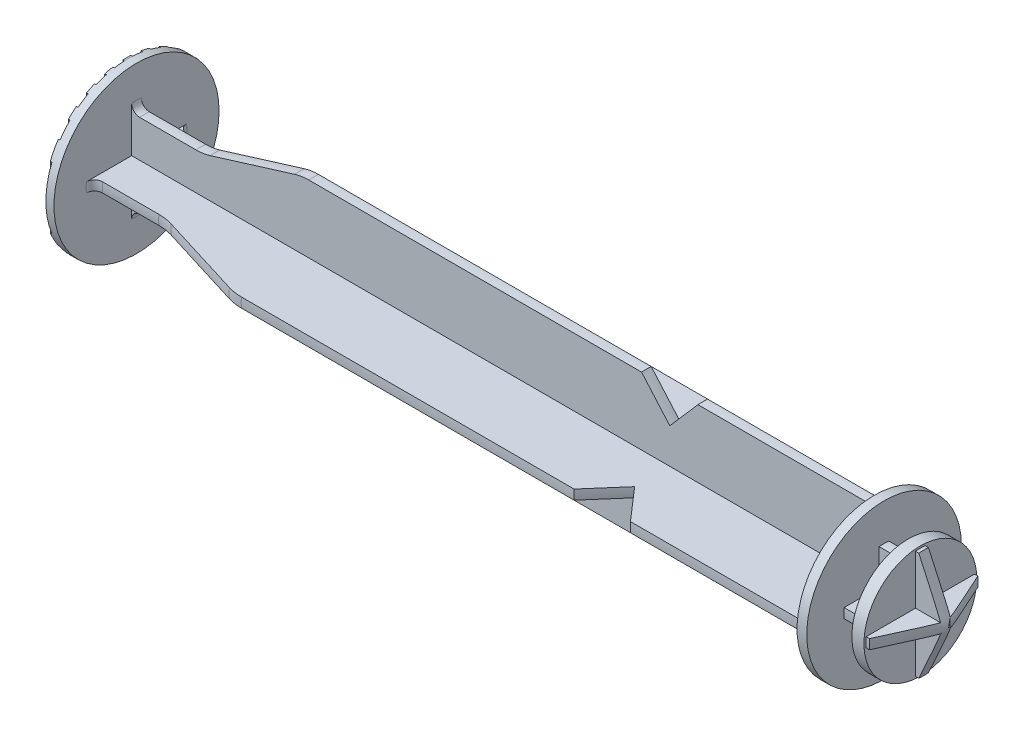
SolidWorks part; units mm, degrees
material "Polyethylene Cross-Linked"
ref_plane "Front Plane" through (0, 0, 0) normal (0, 0, 1) x (1, 0, 0)
ref_plane "Top Plane" through (0, 0, 0) normal (0, 1, 0) x (1, 0, 0)
ref_plane "Right Plane" through (0, 0, 0) normal (1, 0, 0) x (0, 0, -1)
sketch "Sketch1" plane through (0, 0, 0) normal (0, 0, 1) x (1, 0, 0)
  line L0 (102, 0) -> (-102, 0) construction
  line L1 (0, 0) -> (0, 10.25)
  line L2 (0, 10.25) -> (1.2, 10.25)
  line L3 (1.2, 10.25) -> (1.2, 6.25)
  line L4 (2.2, 5.25) -> (9.2, 5.25)
  line L5 (10.9633, 5.5149) -> (21.4367, 8.7351)
  line L6 (23.2, 9) -> (64.5, 9)
  line L7 (64.5, 9) -> (68, 5)
  line L8 (68, 5) -> (71.5, 9)
  line L9 (71.5, 9) -> (92.8, 9)
  line L10 (92.8, 9) -> (92.8, 9.6)
  line L11 (92.8, 9.6) -> (94, 9.6)
  line L12 (94, 9.6) -> (94, 5)
  line L13 (94, 5) -> (97, 5)
  line L14 (97, 5) -> (97, 7)
  line L15 (97, 7) -> (98.8, 7)
  line L16 (98.8, 7) -> (102, 0)
  line L17 (0, 0) -> (102, 0)
  arc A0 (1.2, 6.25) -> (2.2, 5.25) centre (2.2, 6.25) ccw
  arc A1 (21.4367, 8.7351) -> (23.2, 9) centre (23.2, 3) cw
  arc A2 (9.2, 5.25) -> (10.9633, 5.5149) centre (9.2, 11.25) ccw
  point P3 (0, 0)
  point P4 (0, 0)
  dimension "D14" = 1
  dimension "D15" = 6
  dimension "D1" = 1.2
  dimension "D2" = 8
  dimension "D3" = 20.5
  dimension "D4" = 10.5
  dimension "D5" = 102
  dimension "D6" = 10
  dimension "D7" = 7
  dimension "D8" = 18
  dimension "D9" = 19.2
  dimension "D10" = 10
  dimension "D11" = 14
  dimension "D12" = 34
  dimension "D13" = 5
  dimension "D16" = 8
  dimension "D17" = 22
  dimension "D18" = 3.2
revolve "Revolve1" add sketch "Sketch1" angle 360 about L0
sketch "Sketch2" plane through (1.2, 0, 0) normal (1, 0, 0) x (0, 0, -1)
  line L0 (17.7295, 0) -> (-17.7295, 0) construction
  line L1 (0, -17.5817) -> (0, 17.5817) construction
  line L2 (-0.6, 10.2324) -> (-0.6, 0.6)
  line L3 (-0.6, 0.6) -> (-10.2324, 0.6)
  line L4 (0.6, 0.6) -> (0.6, 10.2324)
  line L5 (10.2324, 0.6) -> (0.6, 0.6)
  line L6 (0.6, -0.6) -> (10.2324, -0.6)
  line L7 (0.6, -10.2324) -> (0.6, -0.6)
  line L8 (-0.6, -0.6) -> (-0.6, -10.2324)
  line L9 (-10.2324, -0.6) -> (-0.6, -0.6)
  circle A0 centre (0, 0) radius 10.25 construction
  arc A1 (-10.2324, 0.6) -> (-10.2324, -0.6) centre (0, 0) ccw
  arc A2 (0.6, 10.2324) -> (-0.6, 10.2324) centre (0, 0) ccw
  arc A3 (10.2324, -0.6) -> (10.2324, 0.6) centre (0, 0) ccw
  arc A4 (-0.6, -10.2324) -> (0.6, -10.2324) centre (0, 0) ccw
  point P5 (0, 0)
  point P9 (0, 0)
  point P27 (0, 0)
  dimension "D3" = 1.2
  dimension "D2" = 4
extrude "Cut-Extrude1" cut sketch "Sketch2" along normal up to surface (91.6 mm away) flip side to cut up to face at (92.8, 0, -9)
sketch "Sketch3" plane through (0, 0, 0) normal (-1, 0, 0) x (0, 0, 1)
  line L0 (2.75, -10.2378) -> (1.75, -10.2378)
  line L1 (0.5, -10.2378) -> (-0.5, -10.2378)
  line L2 (0.5, -10.2378) -> (0.5, 10.2378)
  line L3 (0.5, 10.2378) -> (-0.5, 10.2378)
  line L4 (-0.5, -10.2378) -> (-0.5, 10.2378)
  line L5 (0.5, -10.2378) -> (-0.5, 10.2378) construction
  line L6 (0.5, 10.2378) -> (-0.5, -10.2378) construction
  line L7 (1.75, -10.2378) -> (1.75, 10.2378)
  line L8 (2.75, 10.2378) -> (1.75, 10.2378)
  line L9 (2.75, -10.2378) -> (2.75, 10.2378)
  line L10 (5, -10.2378) -> (4, -10.2378)
  line L11 (4, -10.2378) -> (4, 10.2378)
  line L12 (5, 10.2378) -> (4, 10.2378)
  line L13 (5, -10.2378) -> (5, 10.2378)
  line L14 (7.25, -10.2378) -> (6.25, -10.2378)
  line L15 (6.25, -10.2378) -> (6.25, 10.2378)
  line L16 (7.25, 10.2378) -> (6.25, 10.2378)
  line L17 (7.25, -10.2378) -> (7.25, 10.2378)
  line L18 (9.5, -10.2378) -> (8.5, -10.2378)
  line L19 (8.5, -10.2378) -> (8.5, 10.2378)
  line L20 (9.5, 10.2378) -> (8.5, 10.2378)
  line L21 (9.5, -10.2378) -> (9.5, 10.2378)
  line L22 (11.75, -10.2378) -> (10.75, -10.2378)
  line L23 (10.75, -10.2378) -> (10.75, 10.2378)
  line L24 (11.75, 10.2378) -> (10.75, 10.2378)
  line L25 (11.75, -10.2378) -> (11.75, 10.2378)
  line L26 (14, -10.2378) -> (13, -10.2378)
  line L27 (13, -10.2378) -> (13, 10.2378)
  line L28 (14, 10.2378) -> (13, 10.2378)
  line L29 (14, -10.2378) -> (14, 10.2378)
  line L30 (-1.75, -10.2378) -> (-2.75, -10.2378)
  line L31 (-2.75, -10.2378) -> (-2.75, 10.2378)
  line L32 (-1.75, 10.2378) -> (-2.75, 10.2378)
  line L33 (-1.75, -10.2378) -> (-1.75, 10.2378)
  line L34 (-4, -10.2378) -> (-5, -10.2378)
  line L35 (-5, -10.2378) -> (-5, 10.2378)
  line L36 (-4, 10.2378) -> (-5, 10.2378)
  line L37 (-4, -10.2378) -> (-4, 10.2378)
  line L38 (-6.25, -10.2378) -> (-7.25, -10.2378)
  line L39 (-7.25, -10.2378) -> (-7.25, 10.2378)
  line L40 (-6.25, 10.2378) -> (-7.25, 10.2378)
  line L41 (-6.25, -10.2378) -> (-6.25, 10.2378)
  line L42 (-8.5, -10.2378) -> (-9.5, -10.2378)
  line L43 (-9.5, -10.2378) -> (-9.5, 10.2378)
  line L44 (-8.5, 10.2378) -> (-9.5, 10.2378)
  line L45 (-8.5, -10.2378) -> (-8.5, 10.2378)
  line L46 (-10.75, -10.2378) -> (-11.75, -10.2378)
  line L47 (-11.75, -10.2378) -> (-11.75, 10.2378)
  line L48 (-10.75, 10.2378) -> (-11.75, 10.2378)
  line L49 (-10.75, -10.2378) -> (-10.75, 10.2378)
  line L50 (-13, -10.2378) -> (-14, -10.2378)
  line L51 (-14, -10.2378) -> (-14, 10.2378)
  line L52 (-13, 10.2378) -> (-14, 10.2378)
  line L53 (-13, -10.2378) -> (-13, 10.2378)
  circle A0 centre (0, 0) radius 10.25 construction
  point P0 (0, 0)
  dimension "D1" = 1
  dimension "D3" = 2.25
  dimension "D2" = 7
  dimension "D4" = 7
extrude "Cut-Extrude2" cut sketch "Sketch3" against normal blind 0.2 flip side to cut
sketch "Sketch4" plane through (94, 0, 0) normal (1, 0, 0) x (0, 0, -1)
  line L8 (0.6, 0.6) -> (0.6, 10.2324)
  line L9 (-0.6, 10.2324) -> (-0.6, 0.6)
  line L10 (-0.6, 0.6) -> (-10.2324, 0.6)
  line L11 (-10.2324, -0.6) -> (-0.6, -0.6)
  line L12 (-0.6, -0.6) -> (-0.6, -10.2324)
  line L13 (0.6, -10.2324) -> (0.6, -0.6)
  line L14 (0.6, -0.6) -> (10.2324, -0.6)
  line L15 (10.2324, 0.6) -> (0.6, 0.6)
  line L16 (0.6, 0.6) -> (0.6, 10.2324)
  line L17 (-0.6, 10.2324) -> (-0.6, 0.6)
  line L18 (-0.6, 0.6) -> (-10.2324, 0.6)
  line L19 (-10.2324, -0.6) -> (-0.6, -0.6)
  line L20 (-0.6, -0.6) -> (-0.6, -10.2324)
  line L21 (0.6, -10.2324) -> (0.6, -0.6)
  line L22 (0.6, -0.6) -> (10.2324, -0.6)
  line L23 (10.2324, 0.6) -> (0.6, 0.6)
  arc A4 (0.6, 10.2324) -> (-0.6, 10.2324) centre (0, 0) ccw
  arc A5 (-10.2324, 0.6) -> (-10.2324, -0.6) centre (0, 0) ccw
  arc A6 (-0.6, -10.2324) -> (0.6, -10.2324) centre (0, 0) ccw
  arc A7 (10.2324, -0.6) -> (10.2324, 0.6) centre (0, 0) ccw
  arc A8 (0.6, 10.2324) -> (-0.6, 10.2324) centre (0, 0) ccw
  arc A9 (-10.2324, 0.6) -> (-10.2324, -0.6) centre (0, 0) ccw
  arc A10 (-0.6, -10.2324) -> (0.6, -10.2324) centre (0, 0) ccw
  arc A11 (10.2324, -0.6) -> (10.2324, 0.6) centre (0, 0) ccw
  dimension "D1" = 0
extrude "Cut-Extrude3" cut sketch "Sketch4" along normal up to surface (3 mm away) flip side to cut up to face at (97, 0, -5)
ref_plane "Plane1" through (102, 0, 0) normal (1, 0, 0) x (0, 0, -1)
sketch "Sketch5" plane through (102, 0, 0) normal (1, 0, 0) x (0, 0, -1)
  line L8 (0.6, 0.6) -> (0.6, 10.2324)
  line L9 (-0.6, 10.2324) -> (-0.6, 0.6)
  line L10 (-0.6, 0.6) -> (-10.2324, 0.6)
  line L11 (-10.2324, -0.6) -> (-0.6, -0.6)
  line L12 (-0.6, -0.6) -> (-0.6, -10.2324)
  line L13 (0.6, -10.2324) -> (0.6, -0.6)
  line L14 (0.6, -0.6) -> (10.2324, -0.6)
  line L15 (10.2324, 0.6) -> (0.6, 0.6)
  line L16 (0.6, 0.6) -> (0.6, 6.7233)
  line L17 (-0.6, 6.7233) -> (-0.6, 0.6)
  line L18 (-0.6, 0.6) -> (-6.7233, 0.6)
  line L19 (-6.7233, -0.6) -> (-0.6, -0.6)
  line L20 (-0.6, -0.6) -> (-0.6, -6.7233)
  line L21 (0.6, -6.7233) -> (0.6, -0.6)
  line L22 (0.6, -0.6) -> (6.7233, -0.6)
  line L23 (6.7233, 0.6) -> (0.6, 0.6)
  arc A0 (-6.7233, 0.6) -> (-6.7233, -0.6) centre (0, 0) ccw
  arc A1 (6.7233, -0.6) -> (6.7233, 0.6) centre (0, 0) ccw
  arc A2 (0.6, 6.7233) -> (-0.6, 6.7233) centre (0, 0) ccw
  arc A3 (-0.6, -6.7233) -> (0.6, -6.7233) centre (0, 0) ccw
  arc A4 (0.6, 10.2324) -> (-0.6, 10.2324) centre (0, 0) ccw
  arc A5 (-10.2324, 0.6) -> (-10.2324, -0.6) centre (0, 0) ccw
  arc A6 (-0.6, -10.2324) -> (0.6, -10.2324) centre (0, 0) ccw
  arc A7 (10.2324, -0.6) -> (10.2324, 0.6) centre (0, 0) ccw
  dimension "D2" = 13.5
  dimension "D1" = 0
extrude "Cut-Extrude4" cut sketch "Sketch5" against normal blind 3.5 flip side to cut
